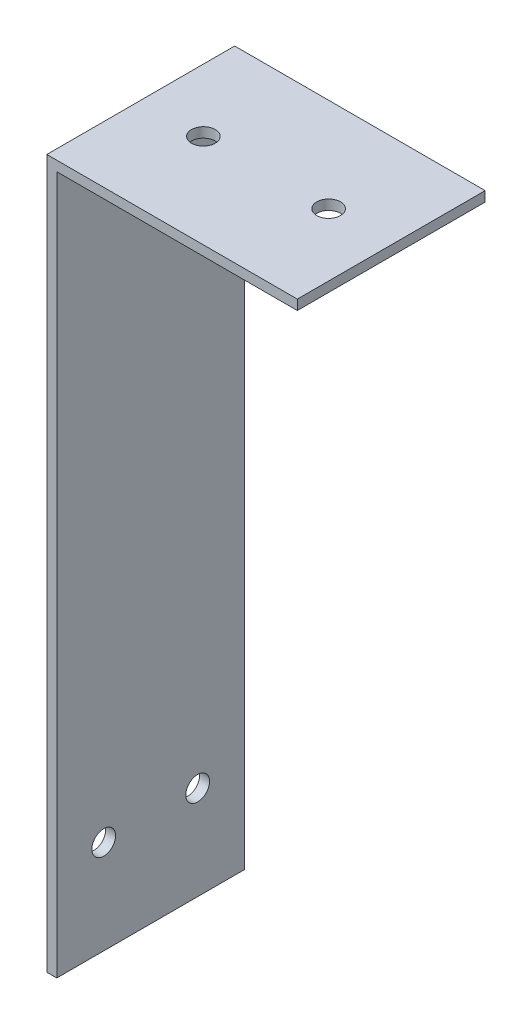
SolidWorks part; units mm, degrees
ref_plane "Front Plane" through (0, 0, 0) normal (0, 0, 1) x (1, 0, 0)
ref_plane "Top Plane" through (0, 0, 0) normal (0, 1, 0) x (1, 0, 0)
ref_plane "Right Plane" through (0, 0, 0) normal (1, 0, 0) x (0, 0, -1)
sketch "Sketch1" plane through (0, 0, 0) normal (0, 0, 1) x (1, 0, 0)
  line L0 (0, 0) -> (0, 113.1)
  line L1 (0, 113.1) -> (40, 113.1)
  line L2 (1.5875, 0) -> (1.5875, 111.5125)
  line L3 (1.5875, 111.5125) -> (40, 111.5125)
  line L4 (40, 113.1) -> (40, 111.5125)
  line L5 (1.5875, 0) -> (0, 0)
  dimension "D2" = 40
  dimension "D3" = 1.5875
  dimension "D1" = 113.1
extrude "Boss-Extrude1" add sketch "Sketch1" along normal mid plane 30
hole_wizard "#6 Clearance Hole1" positions "Sketch3" profile "Sketch2" hole size "#6" standard "ANSI Inch" end condition through all
sketch "Sketch3" plane through (0, 0, 0) normal (-1, 0, 0) x (0, 0, 1)
  line L0 (0, 0) -> (0, 113.1) construction
  line L1 (15, 113.1) -> (-15, 113.1) construction
  point P0 (-7.5, 15)
  point P18 (7.5, 15)
  dimension "D1" = 15
  dimension "D2" = 7.5
sketch "Sketch2" plane through (0, 15, -7.5) normal (0, 1, 0) x (0, 0, 1)
  line L0 (0, 0) -> (0, 40)
  line L1 (0, 40) -> (1.8986, 40)
  line L2 (1.8986, 40) -> (1.8986, 0)
  line L5 (1.8986, 0) -> (0, 0)
  line L11 (0, -6.35) -> (0, 107.95) construction
  dimension "Thru Hole Dia." = 3.7973
  dimension "Thru Hole Depth" = 40
hole_wizard "#6 Clearance Hole2" positions "Sketch5" profile "Sketch6" hole size "#6" standard "ANSI Inch"
sketch "Sketch5" plane through (0, 113.1, 0) normal (0, 1, 0) x (1, 0, 0)
  line L0 (0, -15) -> (0, 15) construction
  line L4 (20, -15) -> (20, 15) construction
  line L5 (40, -15) -> (0, -15) construction
  line L6 (40, 15) -> (0, 15) construction
  line L7 (0, 0) -> (40, 0) construction
  line L8 (40, -15) -> (40, 15) construction
  point P0 (10, 0)
  point P3 (0, 0)
  point P31 (30, 0)
  dimension "D1" = 10
sketch "Sketch6" plane through (10, 113.1, 0) normal (1, 0, 0) x (0, 0, 1)
  line L0 (0, 0) -> (0, 2.7273)
  line L1 (0, 2.7273) -> (1.8986, 1.5865)
  line L2 (1.8986, 1.5865) -> (1.8986, 0)
  line L5 (1.8986, 0) -> (0, 0)
  line L10 (0, 2.7273) -> (-1.8987, 1.5865) construction
  line L11 (0, -6.35) -> (0, 107.95) construction
  dimension "Hole Dia." = 3.7973
  dimension "Hole Depth" = 1.5865
  dimension "Drill Angle" = 118
